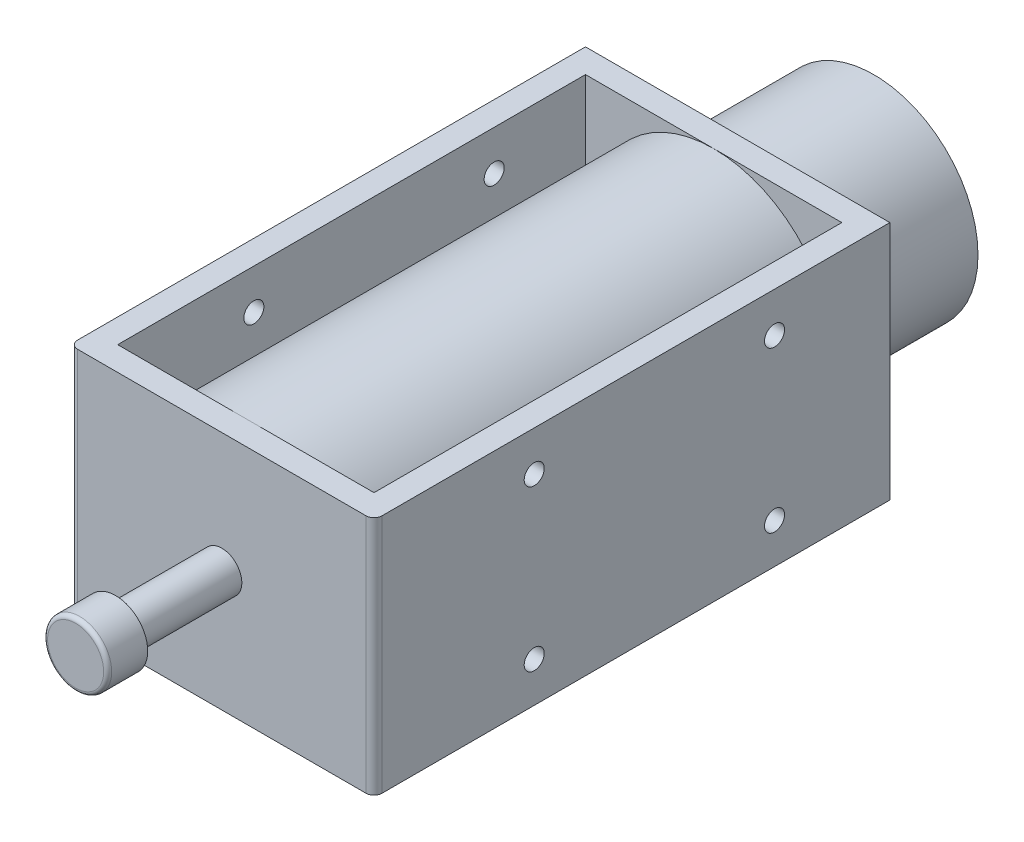
SolidWorks part; units mm, degrees
material "Plain Carbon Steel"
ref_plane "Front Plane" through (0, 0, 0) normal (0, 0, 1) x (1, 0, 0)
ref_plane "Top Plane" through (0, 0, 0) normal (0, 1, 0) x (1, 0, 0)
ref_plane "Right Plane" through (0, 0, 0) normal (1, 0, 0) x (0, 0, -1)
sketch "Sketch1" plane through (0, 0, 0) normal (0, 0, 1) x (1, 0, 0)
  line L1 (-19, -15) -> (19, -15)
  line L2 (-19, -15) -> (-19, 15)
  line L3 (-19, 15) -> (19, 15)
  line L4 (19, -15) -> (19, 15)
  line L5 (-19, -15) -> (19, 15) construction
  line L6 (-19, 15) -> (19, -15) construction
  point P0 (0, 0)
  dimension "D1" = 30
  dimension "D2" = 38
extrude "Boss-Extrude1" add sketch "Sketch1" along normal blind 64.4
sketch "Sketch2" plane through (0, 0, 64.4) normal (0, 0, 1) x (1, 0, 0)
  circle A0 centre (0, 0) radius 4
  dimension "D1" = 8
sketch "Sketch3" plane through (0, 0, 0) normal (0, 0, -1) x (-1, 0, 0)
  circle A0 centre (0, 0) radius 13
  dimension "D1" = 26
extrude "Boss-Extrude3" add sketch "Sketch3" along normal blind 17
extrude "Boss-Extrude4" add sketch "Sketch2" along normal blind 18.25
sketch "Sketch16" plane through (0, -15, 0) normal (0, -1, 0) x (1, 0, 0)
  line L16 (16, 61.4) -> (-16, 61.4)
  line L17 (16, 3) -> (16, 61.4)
  line L18 (-16, 3) -> (16, 3)
  line L19 (-16, 61.4) -> (-16, 3)
  line L20 (16, 61.4) -> (-16, 61.4)
  line L21 (16, 3) -> (16, 61.4)
  line L22 (-16, 3) -> (16, 3)
  line L23 (-16, 61.4) -> (-16, 3)
  dimension "D1" = 3
extrude "Cut-Extrude1" cut sketch "Sketch16" against normal through all
sketch "Sketch17" plane through (0, 0, 61.4) normal (0, 0, -1) x (-1, 0, 0)
  line L0 (-16, -15) -> (16, -15) construction
  circle A0 centre (0, 0) radius 15
extrude "Boss-Extrude9" add sketch "Sketch17" along normal up to surface (58.4 mm away) up to face at (0, 0, 3)
fillet "Fillet1" radius 1 2 edges at (19, 0, 64.4) (-19, 0, 64.4)
hole_wizard "M3x0.5 Tapped Hole1" positions "Sketch18" profile "Sketch19" tap size "M3x0.5" standard "ANSI Metric"
sketch "Sketch18" plane through (-19, 0, 0) normal (-1, 0, 0) x (0, 0, 1)
  line L0 (64.4, 15) -> (64.4, -15) construction
  line L1 (0, 0) -> (63.4, 0) construction
  line L2 (0, 15) -> (0, -15) construction
  line L3 (63.4, -15) -> (63.4, 15) construction
  point P0 (14.4, -10)
  point P6 (44.4, -10)
  point P21 (44.4, 10)
  point P22 (14.4, 10)
  dimension "D1" = 20
  dimension "D2" = 30
  dimension "D3" = 10
  dimension "D4" = 10
sketch "Sketch19" plane through (-19, -10, 14.4) normal (0, 1, 0) x (0, 0, 1)
  line L0 (0, 0) -> (0, 3)
  line L1 (0, 3) -> (1.25, 3)
  line L2 (1.25, 3) -> (1.25, 0)
  line L5 (1.25, 0) -> (0, 0)
  line L11 (0, -6.35) -> (0, 107.95) construction
  dimension "Thru Tap Drill Dia." = 2.5
  dimension "Thru Tap Drill Depth" = 3
cosmetic thread "Hole Thread1" parameters "D2"=3
cosmetic thread "Hole Thread2" parameters "D2"=3
cosmetic thread "Hole Thread3" parameters "D2"=3
cosmetic thread "Hole Thread4" parameters "D2"=3
hole_wizard "M3x0.5 Tapped Hole2" positions "Sketch20" profile "Sketch21" tap size "M3x0.5" standard "ANSI Metric"
sketch "Sketch20" plane through (19, 0, 0) normal (1, 0, 0) x (0, 0, -1)
  point P0 (-14.4, 10)
  point P3 (-14.4, -10)
  point P6 (-44.4, -10)
  point P9 (-44.4, 10)
sketch "Sketch21" plane through (19, 10, 14.4) normal (0, 1, 0) x (0, 0, -1)
  line L0 (0, 0) -> (0, 3)
  line L1 (0, 3) -> (1.25, 3)
  line L2 (1.25, 3) -> (1.25, 0)
  line L5 (1.25, 0) -> (0, 0)
  line L11 (0, -6.35) -> (0, 107.95) construction
  dimension "Thru Tap Drill Dia." = 2.5
  dimension "Thru Tap Drill Depth" = 3
cosmetic thread "Hole Thread5" parameters "D2"=3
cosmetic thread "Hole Thread6" parameters "D2"=3
cosmetic thread "Hole Thread7" parameters "D2"=3
cosmetic thread "Hole Thread8" parameters "D2"=3
sketch "Sketch22" plane through (0, 0, 64.4) normal (0, 0, 1) x (1, 0, 0)
  circle A0 centre (0, 0) radius 2.5
  circle A1 centre (0, 0) radius 4
  circle A2 centre (0, 0) radius 4 construction
  point P5 (-0.2848, -0.2982)
  dimension "D1" = 5
extrude "Cut-Extrude2" cut sketch "Sketch22" along normal offset from surface (13.25 mm away) 5 up to face at (4, 0, 82.65)
fillet "Fillet2" radius 0.5 1 edges at (4, 0, 82.65)
